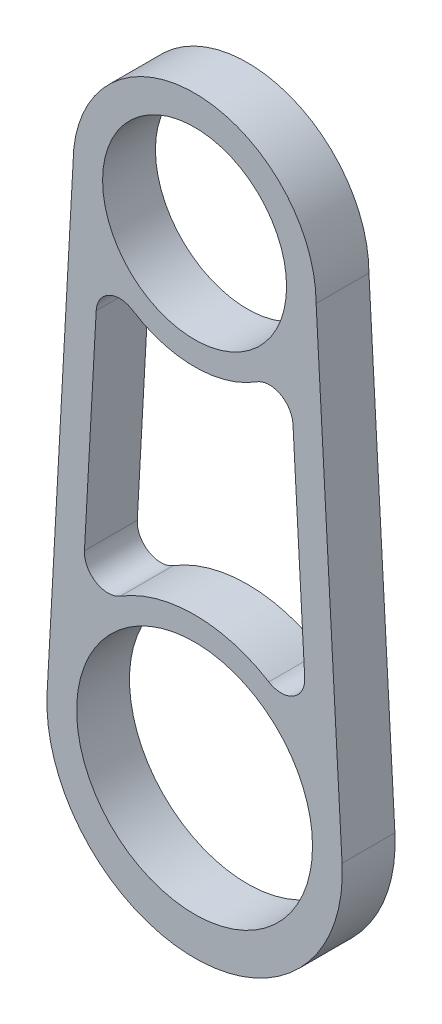
SolidWorks part; units mm, degrees
material "6061-T6 (SS)"
ref_plane "Front Plane" through (0, 0, 0) normal (0, 0, 1) x (1, 0, 0)
ref_plane "Top Plane" through (0, 0, 0) normal (0, 1, 0) x (1, 0, 0)
ref_plane "Right Plane" through (0, 0, 0) normal (1, 0, 0) x (0, 0, -1)
sketch "Sketch1" plane through (0, 0, 0) normal (0, 0, 1) x (1, 0, 0)
  line L0 (0, 0) -> (0, 50.8) construction
  line L1 (-12.7, 0) -> (-9.906, 50.8) construction
  line L2 (12.7, 0) -> (9.906, 50.8) construction
  line L3 (-13.0858, 50.8) -> (-15.8798, 0)
  line L4 (13.0858, 50.8) -> (15.8798, 0)
  line L5 (-15.8798, 0) -> (0, 0) construction
  line L6 (0, 0) -> (15.8798, 0) construction
  line L7 (-13.0858, 50.8) -> (0, 50.8) construction
  line L8 (0, 50.8) -> (13.0858, 50.8) construction
  line L9 (-9.906, 50.8) -> (-12.7, 0)
  line L12 (9.906, 50.8) -> (12.7, 0)
  circle A0 centre (0, 0) radius 12.7
  circle A1 centre (0, 50.8) radius 9.906
  arc A2 (-15.8798, 0) -> (15.8798, 0) centre (0, -0.8734) ccw
  arc A3 (-13.0858, 50.8) -> (13.0858, 50.8) centre (0, 50.8) cw
  circle A6 centre (0, 0) radius 15.24
  circle A7 centre (0, 50.8) radius 12.446
  dimension "D1" = 25.4
  dimension "D2" = 19.812
  dimension "D3" = 50.8
  dimension "D4" = 3.175
  dimension "D5" = 3.175
  dimension "D6" = 2.54
  dimension "D7" = 2.54
extrude "Boss-Extrude1" add sketch "Sketch1" along normal blind 5.6896 contours A3 L3 A2 L4 A1 A0 | L12 A7 L9 A1 | L9 A7 L12 A1 | L12 A6 L9 A0 | L9 A6 L12 A0
fillet "Fillet1" radius 2.54 4 edges at (10.291, 43.8001, 2.8448) (-10.291, 43.8001, 2.8448) (12.1975, 9.1367, 2.8448) (-12.1975, 9.1367, 2.8448)
equation "\"w\"= 700"
equation "\"c to c\"= 2"
equation "\"top hole diameter\"= 0.780"
equation "\"bottom hole diameter\"= 1"
equation "\"MAXo\"= 45000"
equation "\"E\"= 10 * 10 ^ 6"
equation "\"maxd\"= 0.005"
equation "\"1\"= \"w\" * \"c to c\""
equation "\"2\"= \"E\" * \"maxd\""
equation "\"t\"= \"1\" / \"2\""
equation "\"D1@Sketch1\"=\"bottom hole diameter\""
equation "\"D2@Sketch1\"=\"top hole diameter\""
equation "\"D3@Sketch1\"=\"c to c\""
equation "\"offset arround hole\"= .125"
equation "\"thick\"= ( \"t\" ) / \"offset arround hole\""
equation "\"D4@Sketch1\"=\"offset arround hole\""
equation "\"D5@Sketch1\"=\"offset arround hole\""
equation "\"D1@Boss-Extrude1\"=\"thick\""
